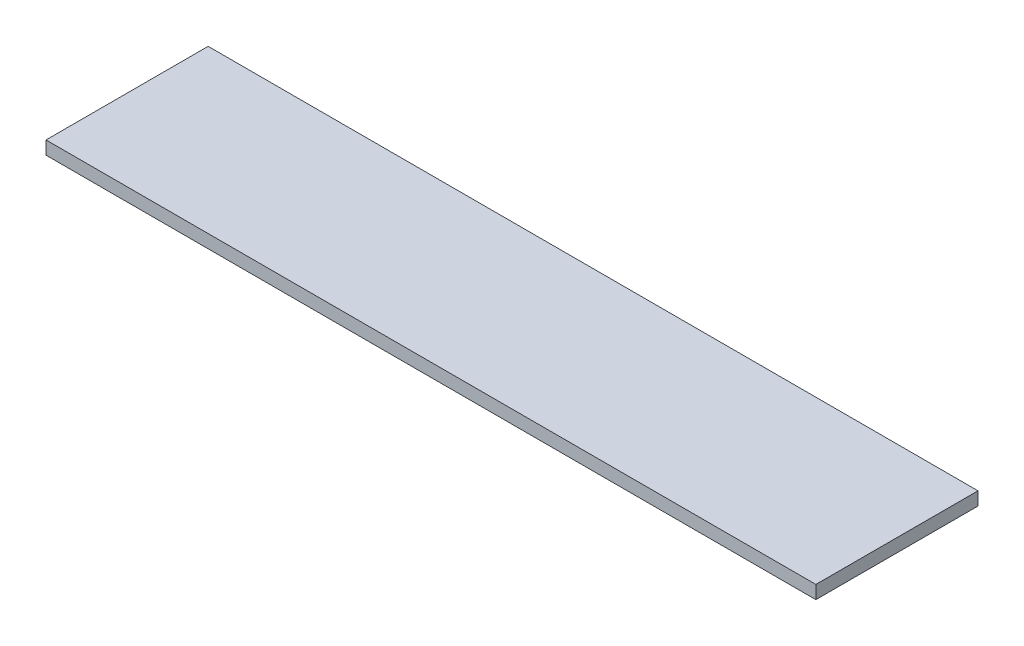
SolidWorks part; units mm, degrees
ref_plane "Спереди" through (0, 0, 0) normal (0, 0, 1) x (1, 0, 0)
ref_plane "Сверху" through (0, 0, 0) normal (0, 1, 0) x (1, 0, 0)
ref_plane "Справа" through (0, 0, 0) normal (1, 0, 0) x (0, 0, -1)
sketch "Эскиз1" plane through (0, 0, 0) normal (0, 0, 1) x (1, 0, 0)
  line L1 (-203.1287, 28.3386) -> (366.6419, 28.3386)
  line L2 (-203.1287, 28.3386) -> (-203.1287, 18.5565)
  line L3 (-203.1287, 18.5565) -> (366.6419, 18.5565)
  line L4 (366.6419, 28.3386) -> (366.6419, 18.5565)
extrude "Бобышка-Вытянуть1" add sketch "Эскиз1" along normal blind 120
